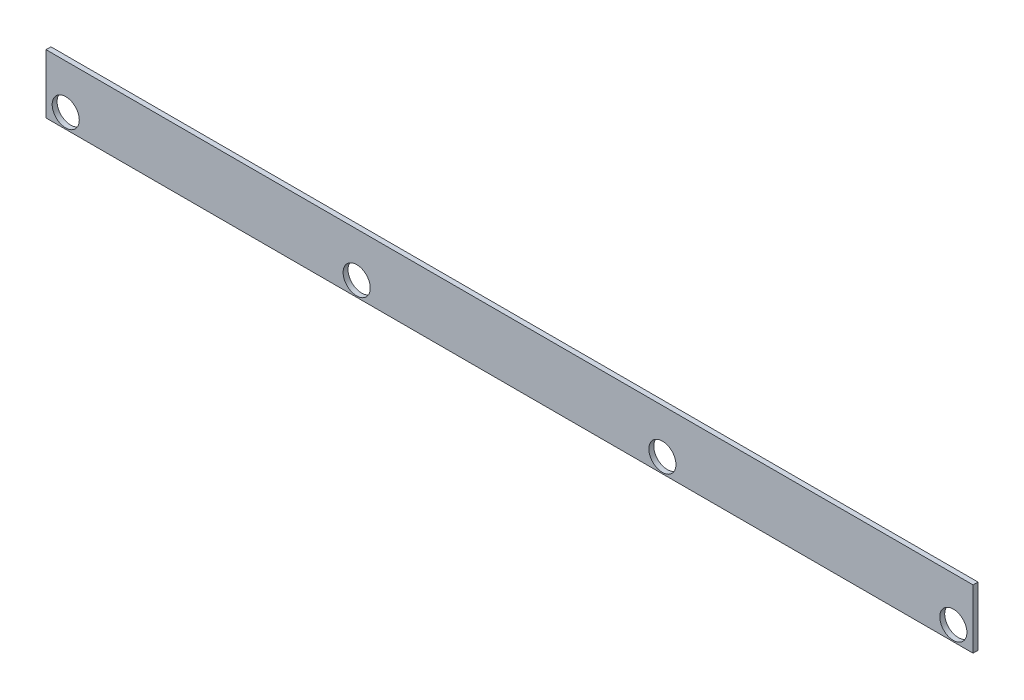
SolidWorks part; units mm, degrees
ref_plane "Front Plane" through (0, 0, 0) normal (0, 0, 1) x (1, 0, 0)
ref_plane "Top Plane" through (0, 0, 0) normal (0, 1, 0) x (1, 0, 0)
ref_plane "Right Plane" through (0, 0, 0) normal (1, 0, 0) x (0, 0, -1)
sketch "M5 floor attachments profile" plane through (0, 0, 0) normal (0, 0, 1) x (1, 0, 0)
  line L0 (-94, -12) -> (94, -12)
  line L1 (94, -12) -> (94, 0)
  line L2 (94, 0) -> (-94, 0)
  line L3 (-94, 0) -> (-94, -12)
  circle A0 centre (-90, -9) radius 2.75
  circle A1 centre (-31, -9) radius 2.75
  circle A2 centre (31, -9) radius 2.75
  circle A3 centre (90, -9) radius 2.75
extrude "M5 floor attachments" add sketch "M5 floor attachments profile" along normal blind 1
